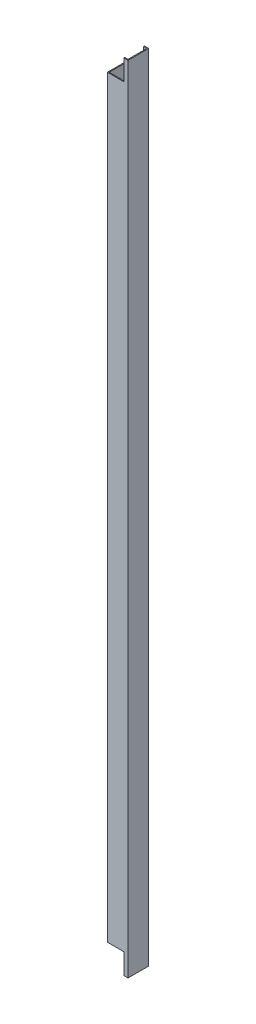
SolidWorks part; units mm, degrees
ref_plane "Front Plane" through (0, 0, 0) normal (0, 0, 1) x (1, 0, 0)
ref_plane "Top Plane" through (0, 0, 0) normal (0, 1, 0) x (1, 0, 0)
ref_plane "Right Plane" through (0, 0, 0) normal (1, 0, 0) x (0, 0, -1)
sketch "Sketch1" plane through (0, 0, 0) normal (0, 1, 0) x (1, 0, 0)
  line L0 (0, 0) -> (0, 50)
  line L1 (0, 50) -> (50, 50)
  line L2 (50, 50) -> (50, 0)
  line L3 (50, 0) -> (0, 0)
  line L4 (2.2, 47.8) -> (47.8, 47.8)
  line L5 (47.8, 47.8) -> (47.8, 2.2)
  line L6 (47.8, 2.2) -> (2.2, 2.2)
  line L7 (2.2, 2.2) -> (2.2, 47.8)
  dimension "D1" = 50
  dimension "D2" = 50
  dimension "D3" = 2.2
extrude "Boss-Extrude1" add sketch "Sketch1" along normal blind 1923
sketch "Sketch2" plane through (0, 0, 0) normal (0, 0, 1) x (1, 0, 0)
  line L0 (0, 0) -> (0, 50)
  line L1 (0, 1923) -> (0, 0) construction
  line L2 (0, 50) -> (40, 50)
  line L3 (40, 50) -> (40, 0)
  line L5 (40, 0) -> (0, 0)
  line L6 (0, 1923) -> (40, 1923)
  line L7 (0, 1923) -> (50, 1923) construction
  line L8 (40, 1923) -> (40, 1873)
  line L9 (40, 1873) -> (0, 1873)
  line L10 (0, 1873) -> (0, 1923)
  dimension "D1" = 50
  dimension "D2" = 40
  dimension "D3" = 50
  dimension "D4" = 40
extrude "Cut-Extrude2" cut sketch "Sketch2" against normal blind 50
equation "\"SquareTube_length\"=1923.0"
equation "\"D1@Boss-Extrude1\"=\"SquareTube_length\""
equation "\"SquareTube_inFront1_cutDepth50_R\"=0.5"
equation "\"D1@Sketch2\" = \"SquareTube_inFront14_cutDepth50_R\""
equation "\"SquareTube_inFront1_cutDepth50_L\"=0.5"
equation "\"D3@Sketch2\" = \"SquareTube_inFront14_cutDepth50_L\""
equation "\"CarBeamWidth\"=700.0"
equation "\"MetalSheet_3mm_length\"=5030.0"
equation "\"MetalSheet_3mm_width\"=1923.0"
equation "\"MetalSheet_3mm_FloorCut_L_length\"=1764.0"
equation "\"MetalSheet_3mm_FloorCut_L_disdance\"=1665.0"
equation "\"MetalSheet_3mm_FloorCut_R_length\"=1764.0"
equation "\"MetalSheet_3mm_FloorCut_R_disdance\"=1665.0"
equation "\"indoorHeight\"=1940.0"
equation "\"x\"=66.0"
equation "\"da\"=62.0"
equation "\"SquareTube_wheel_length\"= 750"
equation "\"channelSteel_length\"=5030.0"
equation "\"SquareTube_inFront2_cutDepth50_R\"=0.5"
equation "\"SquareTube_inFront2_cutDepth50_L\"=0.5"
equation "\"SquareTube_inFront3_cutDepth50_R\"=0.5"
equation "\"SquareTube_inFront3_cutDepth50_L\"=0.5"
equation "\"SquareTube_inFront4_cutDepth50_R\"=0.5"
equation "\"SquareTube_inFront4_cutDepth50_L\"=0.5"
equation "\"SquareTube_inFront5_cutDepth50_R\"=50"
equation "\"SquareTube_inFront5_cutDepth50_L\"=50"
equation "\"SquareTube_inFront6_cutDepth50_R\"=50"
equation "\"SquareTube_inFront6_cutDepth50_L\"=50"
equation "\"SquareTube_inFront7_cutDepth50_R\"=50"
equation "\"SquareTube_inFront7_cutDepth50_L\"=50"
equation "\"SquareTube_inFront8_cutDepth50_R\"=50"
equation "\"SquareTube_inFront8_cutDepth50_L\"=50"
equation "\"SquareTube_inFront9_cutDepth50_R\"=50"
equation "\"SquareTube_inFront9_cutDepth50_L\"=50"
equation "\"SquareTube_inFront10_cutDepth50_R\"=50"
equation "\"SquareTube_inFront10_cutDepth50_L\"=50"
equation "\"SquareTube_inBack1_cutDepth50_R\"=50"
equation "\"SquareTube_inBack1_cutDepth50_L\"=50"
equation "\"SquareTube_inBack2_cutDepth50_R\"=50"
equation "\"SquareTube_inBack2_cutDepth50_L\"=50"
equation "\"SquareTube_inBack3_cutDepth50_R\"=50"
equation "\"SquareTube_inBack3_cutDepth50_L\"=50"
equation "\"SquareTube_inBack4_cutDepth50_R\"=50"
equation "\"SquareTube_inBack4_cutDepth50_L\"=50"
equation "\"SquareTube_inBack5_cutDepth50_R\"=50"
equation "\"SquareTube_inBack5_cutDepth50_L\"=50"
equation "\"SquareTube_inBack6_cutDepth50_R\"=0.5"
equation "\"SquareTube_inBack6_cutDepth50_L\"=0.5"
equation "\"SquareTube_inFront11_cutDepth50_R\"=50"
equation "\"SquareTube_inFront11_cutDepth50_L\"=50"
equation "\"SquareTube_inFront12_cutDepth50_R\"=50"
equation "\"SquareTube_inFront12_cutDepth50_L\"=50"
equation "\"SquareTube_inFront13_cutDepth50_R\"=50"
equation "\"SquareTube_inFront13_cutDepth50_L\"=50"
equation "\"SquareTube_inFront14_cutDepth50_R\"=50"
equation "\"SquareTube_inFront14_cutDepth50_L\"=50"
equation "\"SquareTube_inBack7_cutDepth50_R\"=0.5"
equation "\"SquareTube_inBack7_cutDepth50_L\"=0.5"
equation "\"SquareTube_inBack8_cutDepth50_R\"=0.5"
equation "\"SquareTube_inBack8_cutDepth50_L\"=0.5"
